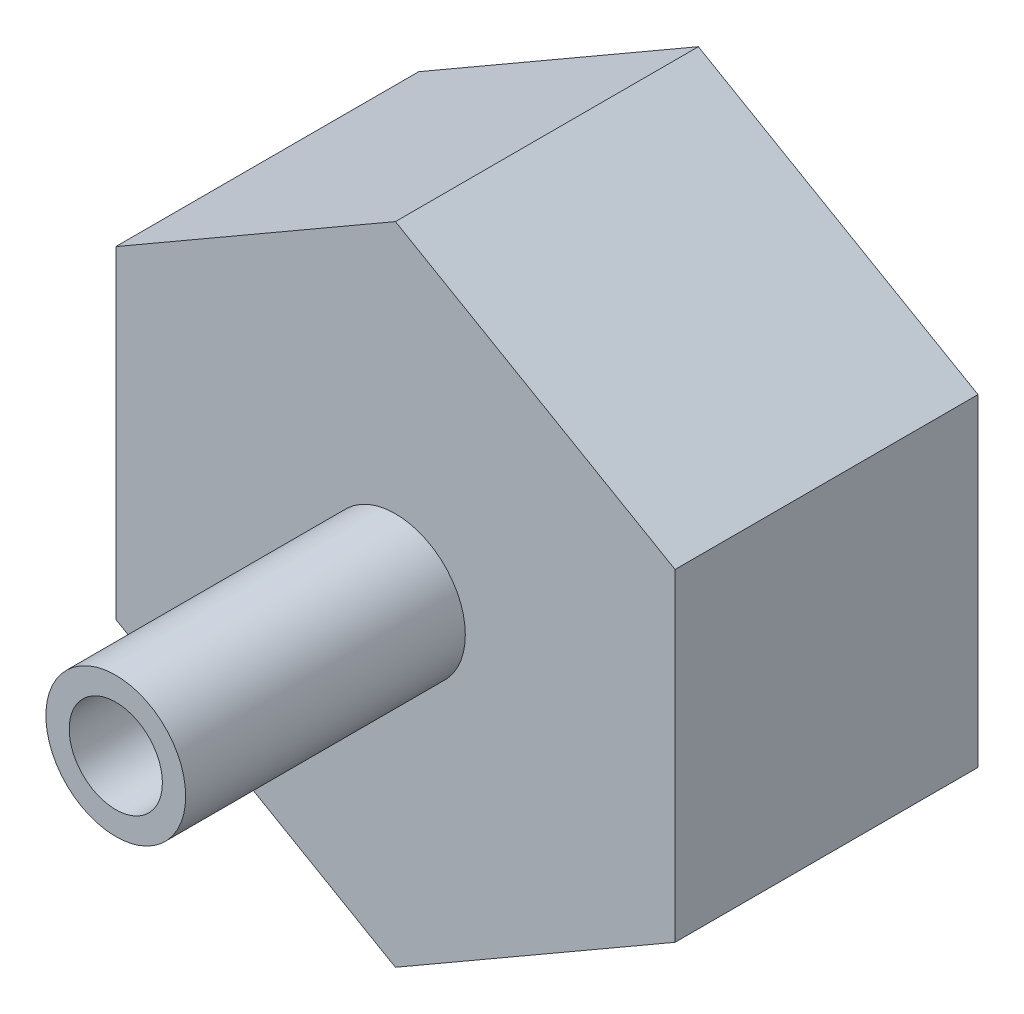
SolidWorks part; units mm, degrees
material "Brass"
ref_plane "Front Plane" through (0, 0, 0) normal (0, 0, 1) x (1, 0, 0)
ref_plane "Top Plane" through (0, 0, 0) normal (0, 1, 0) x (1, 0, 0)
ref_plane "Right Plane" through (0, 0, 0) normal (1, 0, 0) x (0, 0, -1)
other "Configuration Table"
sketch "Sketch1" plane through (0, 0, 0) normal (0, 0, 1) x (1, 0, 0)
  line L0 (12, 6.9282) -> (0, 13.8564)
  line L1 (0, 13.8564) -> (-12, 6.9282)
  line L2 (-12, 6.9282) -> (-12, -6.9282)
  line L3 (-12, -6.9282) -> (0, -13.8564)
  line L4 (0, -13.8564) -> (12, -6.9282)
  line L5 (12, -6.9282) -> (12, 6.9282)
extrude "Hex_Nut" add sketch "Sketch1" along normal blind 13
sketch "Sketch2" plane through (0, 0, 0) normal (0, 0, 1) x (1, 0, 0)
  circle A0 centre (0, 0) radius 10.4775
  dimension "D1" = 20.955
extrude "Thread_Bore" cut sketch "Sketch2" along normal blind 11
sketch "Sketch3" plane through (0, 0, 0) normal (0, 0, 1) x (1, 0, 0)
  circle A0 centre (0, 0) radius 3
  dimension "D1" = 6
extrude "Barb" add sketch "Sketch3" along normal blind 12 from offset 13
sketch "Sketch4" plane through (0, 0, 0) normal (0, 0, 1) x (1, 0, 0)
  circle A0 centre (0, 0) radius 2
  dimension "D1" = 4
extrude "Bore" cut sketch "Sketch4" along normal through all
equation "\"Jar_OD\"= 90  'ASSUMED - Part G fallback - jar outer diameter"
equation "\"Jar_H\"= 120  'ASSUMED - Part G fallback - jar height"
equation "\"Pump_L\"= 45  'ASSUMED - Part G fallback"
equation "\"Pump_W\"= 24  'ASSUMED - Part G fallback"
equation "\"Pump_H\"= 33  'ASSUMED - Part G fallback"
equation "\"Pump_Outlet_OD\"= 7.5  'ASSUMED - Part G fallback"
equation "\"Tube_OD\"= 8  'ASSUMED - Part G fallback"
equation "\"Tube_ID\"= 6  'ASSUMED - Part G fallback"
equation "\"TDS_Body_Dia\"= 12  'ASSUMED - Part G fallback"
equation "\"TDS_Wet_Len\"= 45  'ASSUMED - Part G fallback - length in water"
equation "\"DS_Tube_Dia\"= 6  'ASSUMED - Part G fallback"
equation "\"DS_Tube_Len\"= 50  'ASSUMED - Part G fallback"
equation "\"ORP_Body_Dia\"= 12  'ASSUMED - Part G fallback"
equation "\"ORP_Body_Len\"= 150  'ASSUMED - Part G fallback"
equation "\"ORP_Cap_Dia\"= 16  'ASSUMED - Part G fallback"
equation "\"Turb_W\"= 33  'ASSUMED - Part G fallback - head width"
equation "\"Turb_D\"= 28  'ASSUMED - Part G fallback - head depth"
equation "\"Turb_H\"= 30  'ASSUMED - Part G fallback - head height"
equation "\"Turb_Slot_W\"= 10  'ASSUMED - Part G fallback - slot width"
equation "\"Flow_L\"= 62  'ASSUMED - Part G fallback YF-S201"
equation "\"Flow_W\"= 36  'ASSUMED - Part G fallback"
equation "\"Flow_H\"= 35  'ASSUMED - Part G fallback"
equation "\"Thread_G12_OD\"= 20.955  'ASSUMED - Part G fallback thread G1/2 (major diameter)"
equation "\"Valve_L\"= 75  'ASSUMED - Part G fallback"
equation "\"Valve_W\"= 45  'ASSUMED - Part G fallback"
equation "\"Valve_H\"= 60  'ASSUMED - Part G fallback"
equation "\"Tee_L\"= 40  'ASSUMED - Part G fallback - overall length"
equation "\"Tee_Branch_L\"= 25  'ASSUMED - Part G fallback"
equation "\"Tee_OD\"= 12  'ASSUMED - Part G fallback"
equation "\"Cuv_W\"= 12.5  'ASSUMED - old R3 cuvette (station suppressed in SS4)"
equation "\"Cuv_D\"= 12.5  'ASSUMED - old R3 cuvette (station suppressed in SS4)"
equation "\"Cuv_H\"= 45  'ASSUMED - old R3 cuvette (station suppressed in SS4)"
equation "\"LED_Board_L\"= 20  'ASSUMED - Part G fallback"
equation "\"LED_Board_W\"= 20  'ASSUMED - Part G fallback - LED at centre"
equation "\"GUVA_L\"= 20  'ASSUMED - Part G fallback"
equation "\"GUVA_W\"= 12  'ASSUMED - Part G fallback - sensor at centre"
equation "\"Reed_L\"= 27  'ASSUMED - Part G fallback MC-38 half"
equation "\"Reed_W\"= 14  'ASSUMED - Part G fallback"
equation "\"Reed_H\"= 8  'ASSUMED - Part G fallback"
equation "\"ESP_L\"= 51  'ASSUMED - Part G fallback"
equation "\"ESP_W\"= 28  'ASSUMED - Part G fallback"
equation "\"TFT_L\"= 58  'ASSUMED - Part G fallback - board"
equation "\"TFT_W\"= 35  'ASSUMED - Part G fallback - board"
equation "\"TFT_Win_L\"= 35  'ASSUMED - Part G fallback - visible window"
equation "\"TFT_Win_W\"= 28  'ASSUMED - Part G fallback - visible window"
equation "\"Relay_L\"= 50  'ASSUMED - Part G fallback"
equation "\"Relay_W\"= 26  'ASSUMED - Part G fallback"
equation "\"Relay_H\"= 19  'ASSUMED - Part G fallback"
equation "\"Mosfet_L\"= 34  'ASSUMED - Part G fallback"
equation "\"Mosfet_W\"= 17  'ASSUMED - Part G fallback"
equation "\"Mosfet_H\"= 12  'ASSUMED - Part G fallback"
equation "\"TDS_Board_L\"= 42  'ASSUMED - Part G fallback"
equation "\"TDS_Board_W\"= 32  'ASSUMED - Part G fallback"
equation "\"Turb_Board_L\"= 38  'ASSUMED - Part G fallback"
equation "\"Turb_Board_W\"= 28  'ASSUMED - Part G fallback"
equation "\"BNC_Thread_Dia\"= 9.5  'ASSUMED - Part G fallback"
equation "\"Plate_L\"= 420  'ASSUMED - Part G fallback"
equation "\"Plate_W\"= 297  'ASSUMED - Part G fallback"
equation "\"Plate_T\"= 6  'ASSUMED - Part G fallback"
equation "\"Probe_Clr\"= 0.3  'DESIGN VALUE - Part C rule 3 - printed probe hole = diameter + 0.3"
equation "\"Cuv_Clr\"= 0.2  'DESIGN VALUE - Part C rule 3 - cuvette pocket = size + 0.2"
equation "\"Label_H\"= 0.6  'DESIGN VALUE - Part D - raised label height"
equation "\"D1@Sketch2\" = \"Thread_G12_OD\""
equation "\"D1@Sketch3\" = \"Tube_ID\""
equation "\"Booster_L\"= 150  'ASSUMED - Part G fallback - booster pump"
equation "\"Booster_W\"= 95  'ASSUMED - Part G fallback"
equation "\"Booster_H\"= 100  'ASSUMED - Part G fallback"
equation "\"PTube_OD\"= 6.35  'ASSUMED - Part G fallback - product tube 1/4 inch"
equation "\"Qz_Out\"= 12  'ASSUMED - Part G fallback - quartz channel outside square"
equation "\"Qz_Path\"= 10  'ASSUMED - Part G fallback - quartz channel inside light path"
equation "\"Qz_L\"= 40  'ASSUMED - Part G fallback - quartz channel length"
equation "\"LED860_Dia\"= 5  'ASSUMED - Part G fallback - 860 nm LED"
equation "\"BPW_L\"= 5.4  'ASSUMED - Part G fallback - BPW34"
equation "\"BPW_W\"= 4.3  'ASSUMED - Part G fallback - BPW34"
equation "\"Cart_Dia\"= 50  'ASSUMED - Part G fallback - sediment and pre-carbon cartridges"
equation "\"Cart_L\"= 255  'ASSUMED - Part G fallback"
equation "\"UF_Dia\"= 50  'ASSUMED - Part G fallback - UF cartridge"
equation "\"UF_L\"= 260  'ASSUMED - Part G fallback"
equation "\"RO_Dia\"= 62  'ASSUMED - Part G fallback - RO membrane housing"
equation "\"RO_L\"= 300  'ASSUMED - Part G fallback"
equation "\"UVC_Dia\"= 40  'ASSUMED - Part G fallback - UV-C chamber"
equation "\"UVC_L\"= 300  'ASSUMED - Part G fallback"
equation "\"Tank_W\"= 260  'ASSUMED - Part G fallback - storage tank"
equation "\"Tank_D\"= 160  'ASSUMED - Part G fallback"
equation "\"Tank_H\"= 300  'ASSUMED - Part G fallback"
equation "\"Cab_W\"= 400  'ASSUMED - Part G fallback - purifier cabinet"
equation "\"Cab_D\"= 270  'ASSUMED - Part G fallback"
equation "\"Cab_H\"= 560  'ASSUMED - Part G fallback"
equation "\"ORP_Board_L\"= 40  'ASSUMED - Part G fallback - ORP buffer board"
equation "\"ORP_Board_W\"= 30  'ASSUMED - Part G fallback"
equation "\"Opt_Board_L\"= 50  'ASSUMED - Part G fallback - optical front-end board"
equation "\"Opt_Board_W\"= 40  'ASSUMED - Part G fallback"
equation "\"Buck_L\"= 43  'ASSUMED - Part G fallback - 12 V to 5 V buck module"
equation "\"Buck_W\"= 21  'ASSUMED - Part G fallback"
equation "\"Buck_H\"= 14  'ASSUMED - Part G fallback"
equation "\"BB_L\"= 165  'ASSUMED - Part G fallback - breadboard (As_Built_R3 only)"
equation "\"BB_W\"= 55  'ASSUMED - Part G fallback"
equation "\"BB_H\"= 10  'ASSUMED - Part G fallback"
